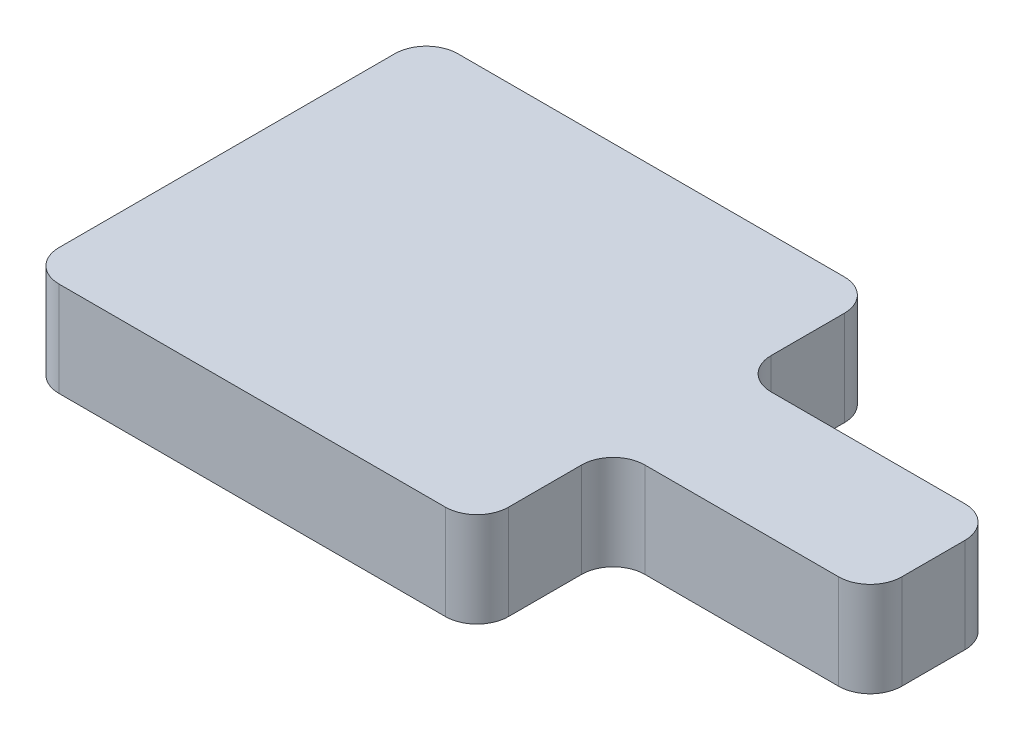
SolidWorks part; units mm, degrees
ref_plane "Front Plane" through (0, 0, 0) normal (0, 0, 1) x (1, 0, 0)
ref_plane "Top Plane" through (0, 0, 0) normal (0, 1, 0) x (1, 0, 0)
ref_plane "Right Plane" through (0, 0, 0) normal (1, 0, 0) x (0, 0, -1)
sketch "Sketch2" plane through (0, 0, 0) normal (0, 1, 0) x (1, 0, 0)
  line L0 (0, 6.35) -> (0, 73.811)
  line L1 (6.35, 0) -> (83.9904, 0)
  line L2 (90.3404, 6.35) -> (90.3404, 21.0305)
  line L3 (96.6904, 27.3805) -> (135.6285, 27.3805)
  line L4 (141.9785, 33.7305) -> (141.9785, 46.4305)
  line L5 (-16.027, 40.0805) -> (157.6855, 40.0805) construction
  line L6 (96.6904, 52.7805) -> (135.6285, 52.7805)
  line L7 (90.3404, 73.811) -> (90.3404, 59.1305)
  line L8 (6.35, 80.161) -> (83.9904, 80.161)
  arc A0 (83.9904, 0) -> (90.3404, 6.35) centre (83.9904, 6.35) ccw
  arc A1 (90.3404, 21.0305) -> (96.6904, 27.3805) centre (96.6904, 21.0305) cw
  arc A2 (141.9785, 33.7305) -> (135.6285, 27.3805) centre (135.6285, 33.7305) cw
  arc A3 (135.6285, 52.7805) -> (141.9785, 46.4305) centre (135.6285, 46.4305) cw
  arc A4 (90.3404, 59.1305) -> (96.6904, 52.7805) centre (96.6904, 59.1305) ccw
  arc A5 (83.9904, 80.161) -> (90.3404, 73.811) centre (83.9904, 73.811) cw
  arc A6 (6.35, 80.161) -> (0, 73.811) centre (6.35, 73.811) ccw
  arc A7 (6.35, 0) -> (0, 6.35) centre (6.35, 6.35) cw
  point P10 (132.4535, 40.0805)
  point P13 (0, 40.0805)
  point P15 (90.3404, 0)
  point P18 (90.3404, 27.3805)
  point P21 (141.9785, 27.3805)
  point P24 (141.9785, 52.7805)
  point P27 (90.3404, 52.7805)
  point P30 (90.3404, 80.161)
  point P33 (0, 80.161)
  point P36 (0, 0)
extrude "Extrude2" add sketch "Sketch2" against normal blind 19.05
